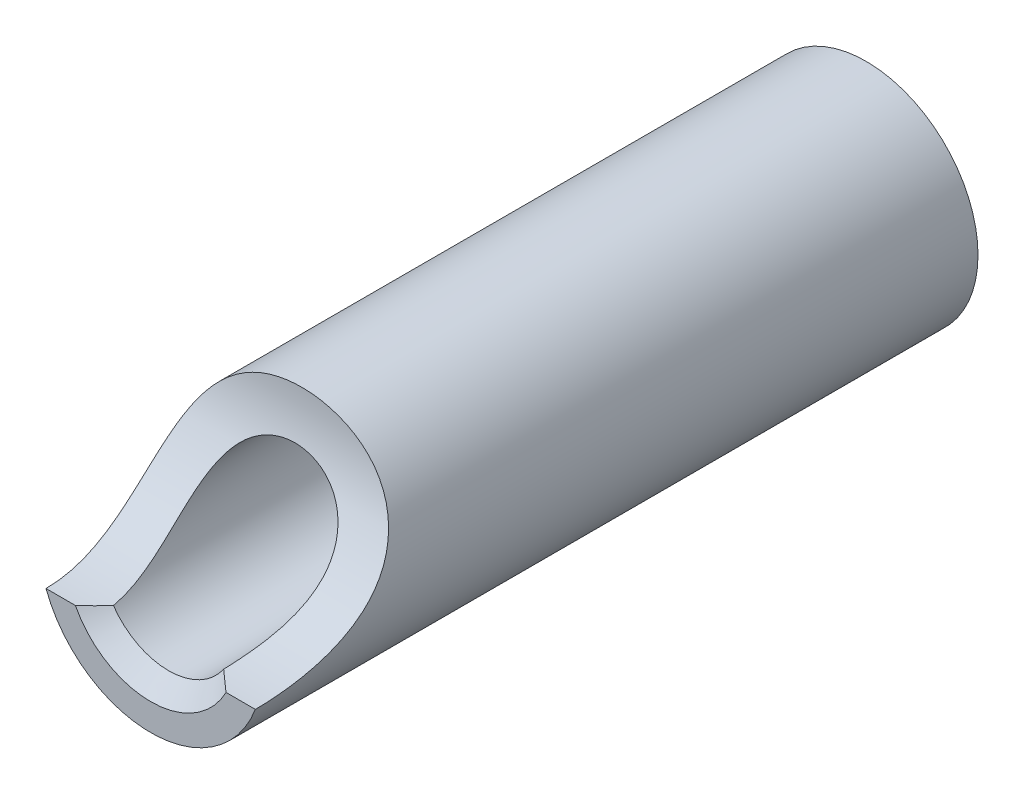
SolidWorks part; units mm, degrees
ref_plane "Front Plane" through (0, 0, 0) normal (0, 0, 1) x (1, 0, 0)
ref_plane "Top Plane" through (0, 0, 0) normal (0, 1, 0) x (1, 0, 0)
ref_plane "Right Plane" through (0, 0, 0) normal (1, 0, 0) x (0, 0, -1)
sketch "Sketch2" plane through (0, 0, 0) normal (0, 0, 1) x (1, 0, 0)
  circle A0 centre (0, 0) radius 4.7625
  circle A1 centre (0, 0) radius 7.9375
  dimension "D1" = 15.875
  dimension "D2" = 9.525
extrude "Boss-Extrude1" add sketch "Sketch2" along normal blind 50.8
chamfer "Chamfer1" distance 1.27 angle 45 2 edges at (4.7625, 0, 0) (4.7625, 0, 50.8)
sketch "Sketch3" plane through (0, 0, 0) normal (1, 0, 0) x (0, 0, -1)
  line L0 (-50.8, 7.9375) -> (-50.8, -7.9375) construction
  circle A0 centre (-50.8, 7.9375) radius 10.7274
  point P3 (-50.8, 7.9375)
  dimension "D1" = 21.4548
extrude "Cut-Extrude1" cut sketch "Sketch3" against normal through all both and the other way through all
